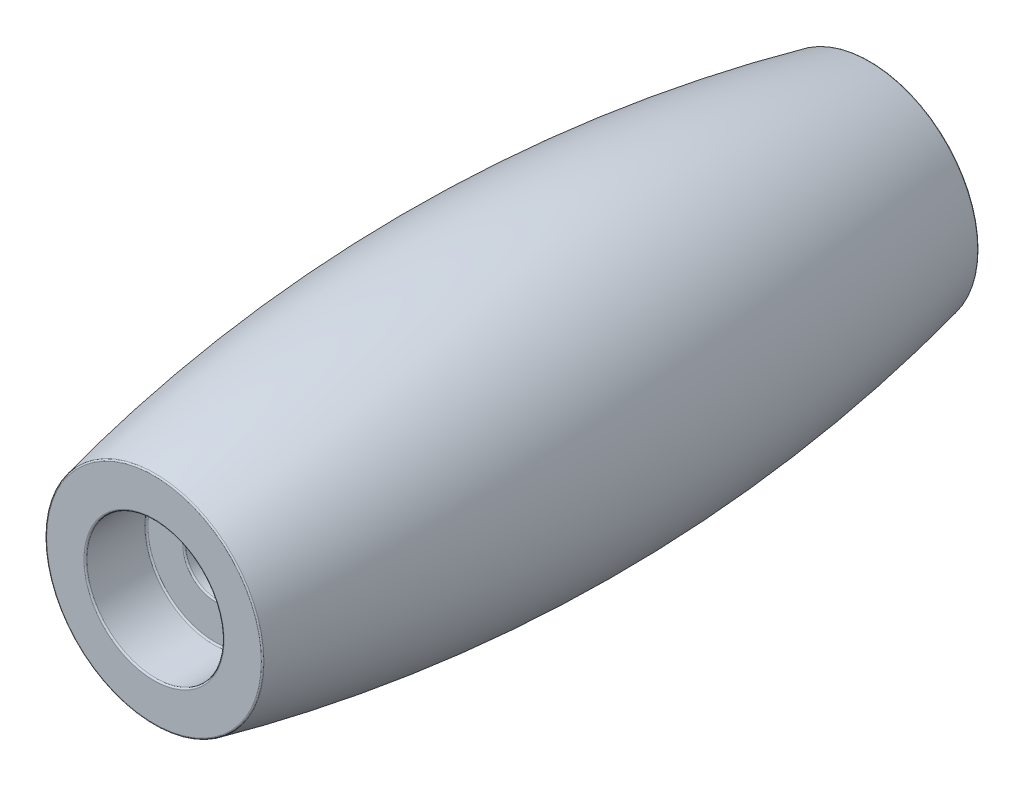
SolidWorks part; units mm, degrees
material "BUTYL"
ref_plane "Front Plane" through (0, 0, 0) normal (0, 0, 1) x (1, 0, 0)
ref_plane "Top Plane" through (0, 0, 0) normal (0, 1, 0) x (1, 0, 0)
ref_plane "Right Plane" through (0, 0, 0) normal (1, 0, 0) x (0, 0, -1)
sketch "Sketch1" plane through (0, 0, 0) normal (0, 1, 0) x (1, 0, 0)
  line L0 (0, 23.5) -> (0, -23.5) construction
  line L1 (9.725, 23.5) -> (9.725, -23.5) construction
  line L2 (0, 0) -> (9.725, 0) construction
  line L3 (2, 19.5) -> (2, -19.5)
  line L4 (4.5, 23.5) -> (4.5, -23.5) construction
  line L5 (2, 19.5) -> (4.5, 19.5)
  line L6 (4.5, 19.5) -> (4.5, 23.5)
  line L7 (2, -19.5) -> (4.5, -19.5)
  line L8 (4.5, -19.5) -> (4.5, -23.5)
  line L9 (7.125, 23.5) -> (7.125, -23.5) construction
  line L10 (4.5, 23.5) -> (7.125, 23.5)
  line L11 (4.5, -23.5) -> (7.125, -23.5)
  arc A0 (7.125, 23.5) -> (7.125, -23.5) centre (-97.7769, 0) cw
  point P2 (0, 0)
  point P10 (2, 0)
  point P13 (4.5, 0)
  point P18 (7.125, 0)
  dimension "D1" = 47
  dimension "D2" = 9.725
  dimension "D3" = 4
  dimension "D4" = 4.5
  dimension "D5" = 4
  dimension "D6" = 7.125
revolve "Revolve1" add sketch "Sketch1" angle 360 about L0
fillet "Fillet1" radius 0.1 8 edges at (-2, 0, -19.5) (-4.5, 0, -19.5) (-4.5, 0, -23.5) (-7.125, 0, -23.5) (-2, 0, 19.5) (-4.5, 0, 19.5) (-4.5, 0, 23.5) (-7.125, 0, 23.5)
